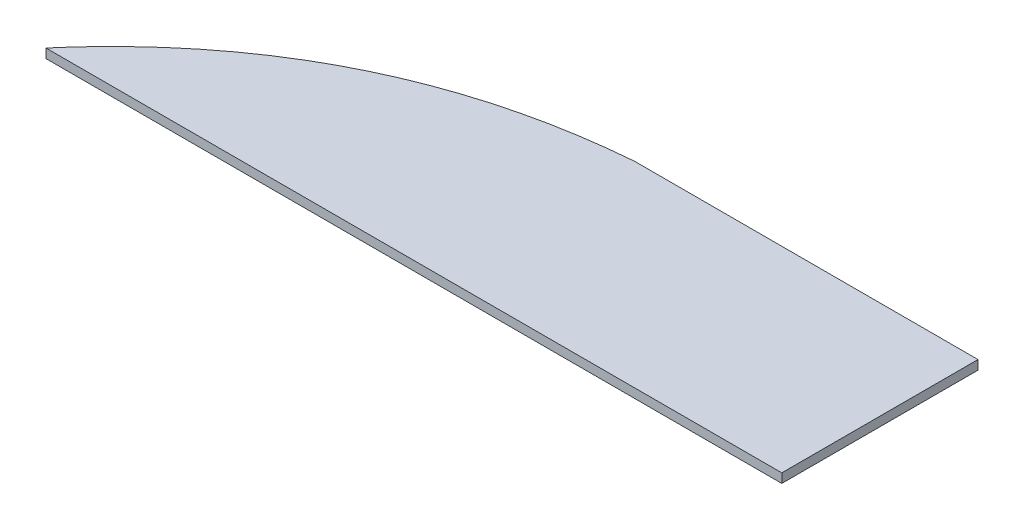
SolidWorks part; units mm, degrees
ref_plane "Front Plane" through (0, 0, 0) normal (0, 0, 1) x (1, 0, 0)
ref_plane "Top Plane" through (0, 0, 0) normal (0, 1, 0) x (1, 0, 0)
ref_plane "Right Plane" through (0, 0, 0) normal (1, 0, 0) x (0, 0, -1)
sketch "Sketch1" plane through (0, 0, 0) normal (0, 1, 0) x (1, 0, 0)
  line L1 (0, 0) -> (381, 0)
  line L2 (0, 0) -> (0, 101.6)
  line L3 (0, 101.6) -> (381, 101.6)
  line L4 (381, 0) -> (381, 101.6)
  dimension "D1" = 101.6
  dimension "D2" = 381
extrude "Boss-Extrude1" add sketch "Sketch1" along normal blind 4.7625
sketch "Sketch2" plane through (0, 4.7625, 0) normal (0, 1, 0) x (1, 0, 0)
  line L0 (381, 101.6) -> (0, 101.6) construction
  line L1 (0, 0) -> (0, 101.6)
  line L2 (0, 101.6) -> (203.2, 101.6)
  spline S0 degree 2 poles (0, 0) (78.2793, 91.4912) (203.2, 101.6) knots 0 0 0 1 1 1
  dimension "D1" = 203.2
extrude "Cut-Extrude1" cut sketch "Sketch2" against normal through all and the other way through all
